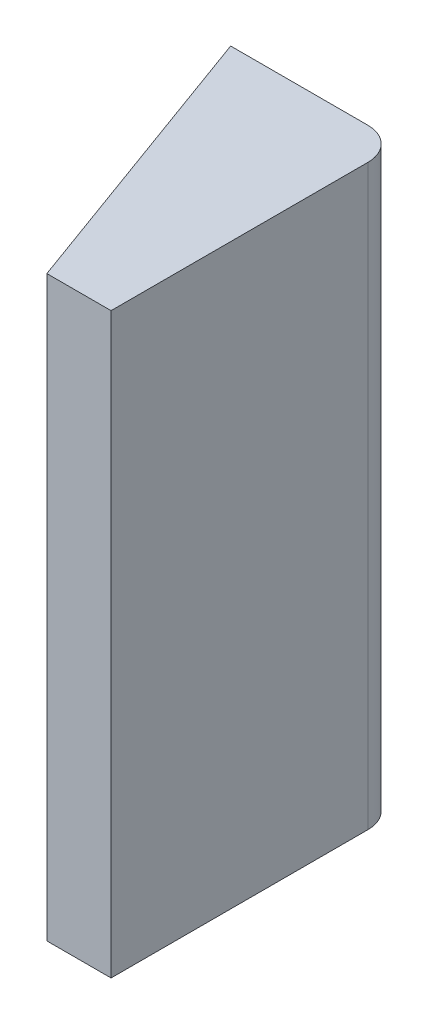
SolidWorks part; units mm, degrees
ref_plane "前视基准面" through (0, 0, 0) normal (0, 0, 1) x (1, 0, 0)
ref_plane "上视基准面" through (0, 0, 0) normal (0, 1, 0) x (1, 0, 0)
ref_plane "右视基准面" through (0, 0, 0) normal (1, 0, 0) x (0, 0, -1)
other "Configuration Table"
sketch "草图1" plane through (0, 0, 0) normal (0, 1, 0) x (1, 0, 0)
  line L0 (0, 0) -> (16.3787, -45)
  line L1 (0, 0) -> (26.3787, 0)
  line L4 (26.3787, 0) -> (26.3787, -45)
  line L5 (16.3787, -45) -> (26.3787, -45)
  dimension "D1" = 70
  dimension "D2" = 10
  dimension "D4" = 45
extrude "凸台-拉伸1" add sketch "草图1" along normal blind 90
fillet "圆角1" radius 5 1 edges at (26.3787, 45, 0)
